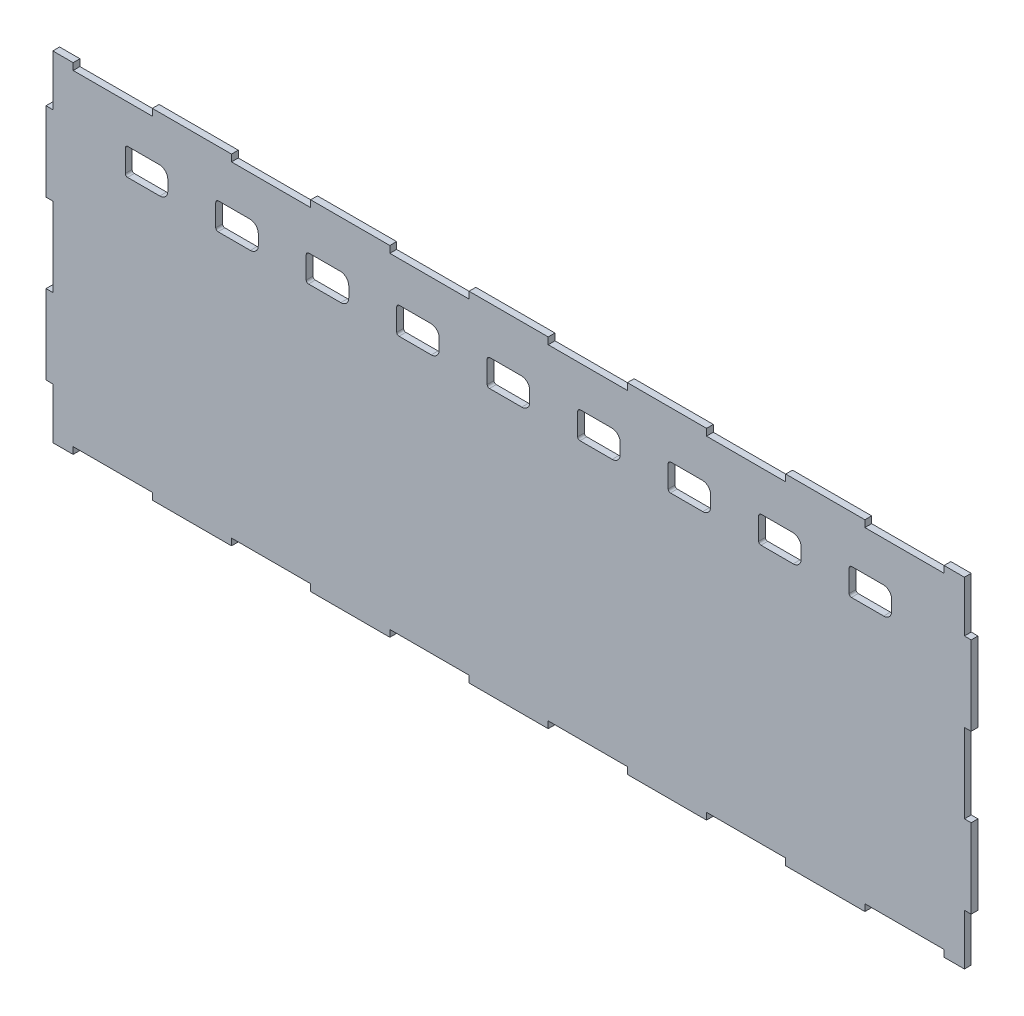
SolidWorks part; units mm, degrees
ref_plane "Front Plane" through (0, 0, 0) normal (0, 0, 1) x (1, 0, 0)
ref_plane "Top Plane" through (0, 0, 0) normal (0, 1, 0) x (1, 0, 0)
ref_plane "Right Plane" through (0, 0, 0) normal (1, 0, 0) x (0, 0, -1)
sketch "Model" plane through (0, 0, 0) normal (0, 0, 1) x (1, 0, 0)
  line L0 (201.5, 75) -> (192.5, 75)
  line L1 (192.5, 75) -> (192.5, 72)
  line L2 (192.5, 72) -> (157.5, 72)
  line L3 (157.5, 72) -> (157.5, 75)
  line L4 (157.5, 75) -> (122.5, 75)
  line L5 (122.5, 75) -> (122.5, 72)
  line L6 (122.5, 72) -> (87.5, 72)
  line L7 (87.5, 72) -> (87.5, 75)
  line L8 (87.5, 75) -> (52.5, 75)
  line L9 (52.5, 75) -> (52.5, 72)
  line L10 (52.5, 72) -> (17.5, 72)
  line L11 (17.5, 72) -> (17.5, 75)
  line L12 (17.5, 75) -> (-17.5, 75)
  line L13 (-17.5, 75) -> (-17.5, 72)
  line L14 (-17.5, 72) -> (-52.5, 72)
  line L15 (-52.5, 72) -> (-52.5, 75)
  line L16 (-52.5, 75) -> (-87.5, 75)
  line L17 (-87.5, 75) -> (-87.5, 72)
  line L18 (-87.5, 72) -> (-122.5, 72)
  line L19 (-122.5, 72) -> (-122.5, 75)
  line L20 (-122.5, 75) -> (-157.5, 75)
  line L21 (-157.5, 75) -> (-157.5, 72)
  line L22 (-157.5, 72) -> (-192.5, 72)
  line L23 (-192.5, 72) -> (-192.5, 75)
  line L24 (-192.5, 75) -> (-201.5, 75)
  line L25 (-201.5, 75) -> (-201.5, 72)
  line L26 (-201.5, 72) -> (-201.5, 52.5)
  line L27 (-201.5, 52.5) -> (-204.5, 52.5)
  line L28 (-204.5, 52.5) -> (-204.5, 17.5)
  line L29 (-204.5, 17.5) -> (-201.5, 17.5)
  line L30 (-201.5, 17.5) -> (-201.5, -17.5)
  line L31 (-201.5, -17.5) -> (-204.5, -17.5)
  line L32 (-204.5, -17.5) -> (-204.5, -52.5)
  line L33 (-204.5, -52.5) -> (-201.5, -52.5)
  line L34 (-201.5, -52.5) -> (-201.5, -72)
  line L35 (-201.5, -72) -> (-201.5, -75)
  line L36 (-201.5, -75) -> (-192.5, -75)
  line L37 (-192.5, -75) -> (-192.5, -72)
  line L38 (-192.5, -72) -> (-157.5, -72)
  line L39 (-157.5, -72) -> (-157.5, -75)
  line L40 (-157.5, -75) -> (-122.5, -75)
  line L41 (-122.5, -75) -> (-122.5, -72)
  line L42 (-122.5, -72) -> (-87.5, -72)
  line L43 (-87.5, -72) -> (-87.5, -75)
  line L44 (-87.5, -75) -> (-52.5, -75)
  line L45 (-52.5, -75) -> (-52.5, -72)
  line L46 (-52.5, -72) -> (-17.5, -72)
  line L47 (-17.5, -72) -> (-17.5, -75)
  line L48 (-17.5, -75) -> (17.5, -75)
  line L49 (17.5, -75) -> (17.5, -72)
  line L50 (17.5, -72) -> (52.5, -72)
  line L51 (52.5, -72) -> (52.5, -75)
  line L52 (52.5, -75) -> (87.5, -75)
  line L53 (87.5, -75) -> (87.5, -72)
  line L54 (87.5, -72) -> (122.5, -72)
  line L55 (122.5, -72) -> (122.5, -75)
  line L56 (122.5, -75) -> (157.5, -75)
  line L57 (157.5, -75) -> (157.5, -72)
  line L58 (157.5, -72) -> (192.5, -72)
  line L59 (192.5, -72) -> (192.5, -75)
  line L60 (192.5, -75) -> (201.5, -75)
  line L61 (201.5, -75) -> (201.5, -72)
  line L62 (201.5, -72) -> (201.5, -52.5)
  line L63 (201.5, -52.5) -> (204.5, -52.5)
  line L64 (204.5, -52.5) -> (204.5, -17.5)
  line L65 (204.5, -17.5) -> (201.5, -17.5)
  line L66 (201.5, -17.5) -> (201.5, 17.5)
  line L67 (201.5, 17.5) -> (204.5, 17.5)
  line L68 (204.5, 17.5) -> (204.5, 52.5)
  line L69 (204.5, 52.5) -> (201.5, 52.5)
  line L70 (201.5, 52.5) -> (201.5, 72)
  line L71 (201.5, 72) -> (201.5, 75)
extrude "Boss-Extrude1" add sketch "Model" along normal blind 3
sketch "Sketch1" plane through (0, 0, 3) normal (0, 0, 1) x (1, 0, 0)
  line L0 (-154.1867, 43.1) -> (-168.4617, 43.1)
  line L1 (-168.2617, 55) -> (-154.3867, 55)
  line L2 (-169.4617, 44.1) -> (-169.4617, 53.8)
  line L3 (-150.6617, 46.625) -> (-150.6617, 51.275)
  line L4 (-114.1867, 42.2832) -> (-128.4617, 42.2832)
  line L5 (-204.5617, 48.1332) -> (-169.4617, 48.1332) construction
  line L6 (-128.2617, 54.1832) -> (-114.3867, 54.1832)
  line L7 (-129.4617, 43.2832) -> (-129.4617, 52.9832)
  line L8 (-110.6617, 45.8082) -> (-110.6617, 50.4582)
  line L9 (-74.1867, 42.2832) -> (-88.4617, 42.2832)
  line L10 (-88.2617, 54.1832) -> (-74.3867, 54.1832)
  line L11 (-89.4617, 43.2832) -> (-89.4617, 52.9832)
  line L12 (-70.6617, 45.8082) -> (-70.6617, 50.4582)
  line L13 (-34.1867, 42.2832) -> (-48.4617, 42.2832)
  line L14 (-48.2617, 54.1832) -> (-34.3867, 54.1832)
  line L15 (-49.4617, 43.2832) -> (-49.4617, 52.9832)
  line L16 (-30.6617, 45.8082) -> (-30.6617, 50.4582)
  line L17 (5.8133, 42.2832) -> (-8.4617, 42.2832)
  line L18 (-8.2617, 54.1832) -> (5.6133, 54.1832)
  line L19 (-9.4617, 43.2832) -> (-9.4617, 52.9832)
  line L20 (9.3383, 45.8082) -> (9.3383, 50.4582)
  line L21 (45.8133, 42.2832) -> (31.5383, 42.2832)
  line L22 (31.7383, 54.1832) -> (45.6133, 54.1832)
  line L23 (30.5383, 43.2832) -> (30.5383, 52.9832)
  line L24 (49.3383, 45.8082) -> (49.3383, 50.4582)
  line L25 (85.8133, 42.2832) -> (71.5383, 42.2832)
  line L26 (71.7383, 54.1832) -> (85.6133, 54.1832)
  line L27 (70.5383, 43.2832) -> (70.5383, 52.9832)
  line L28 (89.3383, 45.8082) -> (89.3383, 50.4582)
  line L29 (125.8133, 42.2832) -> (111.5383, 42.2832)
  line L30 (111.7383, 54.1832) -> (125.6133, 54.1832)
  line L31 (110.5383, 43.2832) -> (110.5383, 52.9832)
  line L32 (129.3383, 45.8082) -> (129.3383, 50.4582)
  line L33 (165.8133, 42.2832) -> (151.5383, 42.2832)
  line L34 (151.7383, 54.1832) -> (165.6133, 54.1832)
  line L35 (150.5383, 43.2832) -> (150.5383, 52.9832)
  line L36 (169.3383, 45.8082) -> (169.3383, 50.4582)
  line L40 (-201.5, 55) -> (-201.5, 75) construction
  arc A0 (-150.6617, 46.625) -> (-154.1867, 43.1) centre (-154.1867, 46.625) cw
  arc A1 (-150.6617, 51.275) -> (-154.3867, 55) centre (-154.3867, 51.275) ccw
  arc A2 (-168.4617, 43.1) -> (-169.4617, 44.1) centre (-168.4617, 44.1) cw
  arc A3 (-169.4617, 53.8) -> (-168.2617, 55) centre (-168.2617, 53.8) cw
  arc A4 (-110.6617, 45.8082) -> (-114.1867, 42.2832) centre (-114.1867, 45.8082) cw
  arc A5 (-110.6617, 50.4582) -> (-114.3867, 54.1832) centre (-114.3867, 50.4582) ccw
  arc A6 (-128.4617, 42.2832) -> (-129.4617, 43.2832) centre (-128.4617, 43.2832) cw
  arc A7 (-129.4617, 52.9832) -> (-128.2617, 54.1832) centre (-128.2617, 52.9832) cw
  arc A8 (-70.6617, 45.8082) -> (-74.1867, 42.2832) centre (-74.1867, 45.8082) cw
  arc A9 (-70.6617, 50.4582) -> (-74.3867, 54.1832) centre (-74.3867, 50.4582) ccw
  arc A10 (-88.4617, 42.2832) -> (-89.4617, 43.2832) centre (-88.4617, 43.2832) cw
  arc A11 (-89.4617, 52.9832) -> (-88.2617, 54.1832) centre (-88.2617, 52.9832) cw
  arc A12 (-30.6617, 45.8082) -> (-34.1867, 42.2832) centre (-34.1867, 45.8082) cw
  arc A13 (-30.6617, 50.4582) -> (-34.3867, 54.1832) centre (-34.3867, 50.4582) ccw
  arc A14 (-48.4617, 42.2832) -> (-49.4617, 43.2832) centre (-48.4617, 43.2832) cw
  arc A15 (-49.4617, 52.9832) -> (-48.2617, 54.1832) centre (-48.2617, 52.9832) cw
  arc A16 (9.3383, 45.8082) -> (5.8133, 42.2832) centre (5.8133, 45.8082) cw
  arc A17 (9.3383, 50.4582) -> (5.6133, 54.1832) centre (5.6133, 50.4582) ccw
  arc A18 (-8.4617, 42.2832) -> (-9.4617, 43.2832) centre (-8.4617, 43.2832) cw
  arc A19 (-9.4617, 52.9832) -> (-8.2617, 54.1832) centre (-8.2617, 52.9832) cw
  arc A20 (49.3383, 45.8082) -> (45.8133, 42.2832) centre (45.8133, 45.8082) cw
  arc A21 (49.3383, 50.4582) -> (45.6133, 54.1832) centre (45.6133, 50.4582) ccw
  arc A22 (31.5383, 42.2832) -> (30.5383, 43.2832) centre (31.5383, 43.2832) cw
  arc A23 (30.5383, 52.9832) -> (31.7383, 54.1832) centre (31.7383, 52.9832) cw
  arc A24 (89.3383, 45.8082) -> (85.8133, 42.2832) centre (85.8133, 45.8082) cw
  arc A25 (89.3383, 50.4582) -> (85.6133, 54.1832) centre (85.6133, 50.4582) ccw
  arc A26 (71.5383, 42.2832) -> (70.5383, 43.2832) centre (71.5383, 43.2832) cw
  arc A27 (70.5383, 52.9832) -> (71.7383, 54.1832) centre (71.7383, 52.9832) cw
  arc A28 (129.3383, 45.8082) -> (125.8133, 42.2832) centre (125.8133, 45.8082) cw
  arc A29 (129.3383, 50.4582) -> (125.6133, 54.1832) centre (125.6133, 50.4582) ccw
  arc A30 (111.5383, 42.2832) -> (110.5383, 43.2832) centre (111.5383, 43.2832) cw
  arc A31 (110.5383, 52.9832) -> (111.7383, 54.1832) centre (111.7383, 52.9832) cw
  arc A32 (169.3383, 45.8082) -> (165.8133, 42.2832) centre (165.8133, 45.8082) cw
  arc A33 (169.3383, 50.4582) -> (165.6133, 54.1832) centre (165.6133, 50.4582) ccw
  arc A34 (151.5383, 42.2832) -> (150.5383, 43.2832) centre (151.5383, 43.2832) cw
  arc A35 (150.5383, 52.9832) -> (151.7383, 54.1832) centre (151.7383, 52.9832) cw
  dimension "D2" = 35.1
extrude "Cut-Extrude1" cut sketch "Sketch1" against normal through all
